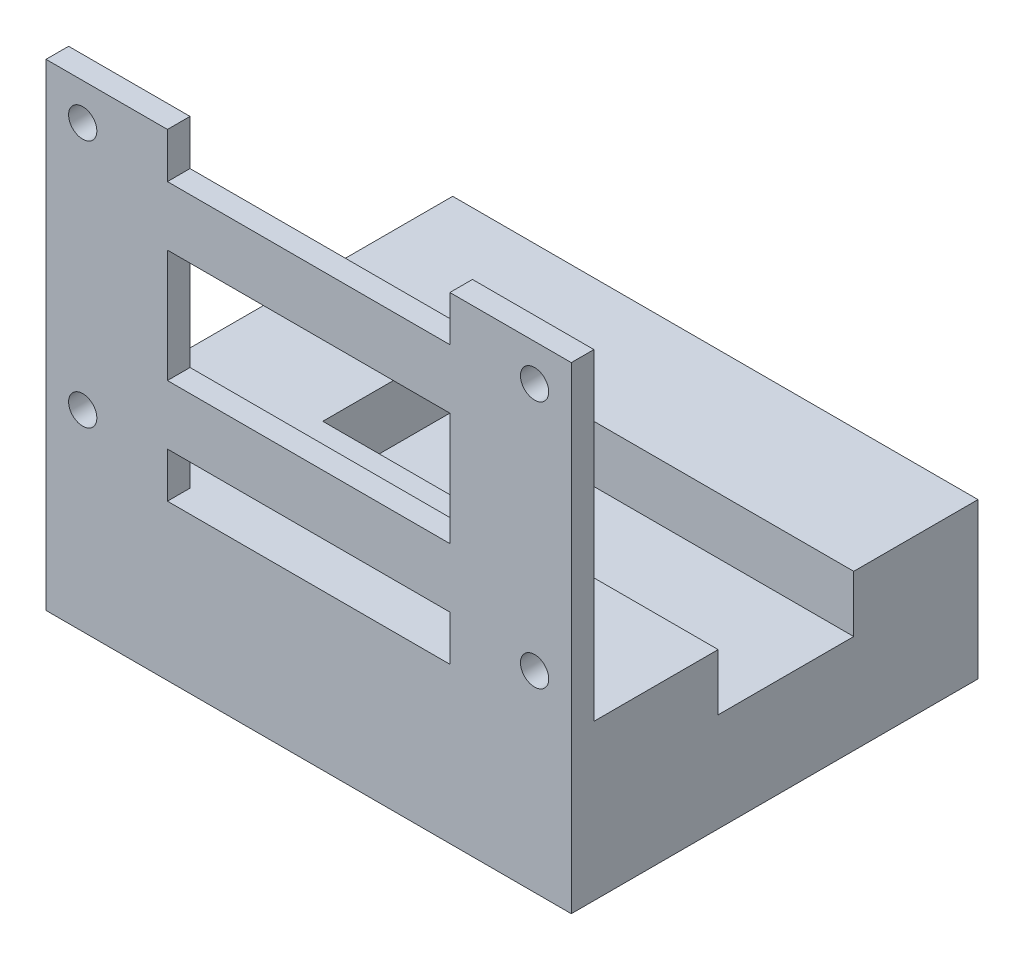
SolidWorks part; units mm, degrees
ref_plane "Front Plane" through (0, 0, 0) normal (0, 0, 1) x (1, 0, 0)
ref_plane "Top Plane" through (0, 0, 0) normal (0, 1, 0) x (1, 0, 0)
ref_plane "Right Plane" through (0, 0, 0) normal (1, 0, 0) x (0, 0, -1)
sketch "Sketch1" plane through (0, 0, 0) normal (0, 1, 0) x (1, 0, 0)
  line L1 (-23.25, -17) -> (23.25, -17)
  line L2 (-23.25, -17) -> (-23.25, 17)
  line L3 (-23.25, 17) -> (23.25, 17)
  line L4 (23.25, -17) -> (23.25, 17)
  line L5 (-23.25, -17) -> (23.25, 17) construction
  line L6 (-23.25, 17) -> (23.25, -17) construction
  point P0 (0, 0)
  dimension "D1" = 46.5
  dimension "D2" = 34
extrude "Boss-Extrude1" add sketch "Sketch1" along normal blind 13.75
sketch "Sketch2" plane through (0, 0, 17) normal (0, 0, 1) x (1, 0, 0)
  line L1 (-23.25, 0) -> (23.25, 0)
  line L2 (-23.25, 0) -> (-23.25, 42.25)
  line L3 (-23.25, 42.25) -> (23.25, 42.25)
  line L4 (23.25, 0) -> (23.25, 42.25)
  dimension "D1" = 46.5
  dimension "D2" = 42.25
extrude "Boss-Extrude2" add sketch "Sketch2" along normal blind 2
sketch "Sketch3" plane through (0, 0, 19) normal (0, 0, 1) x (1, 0, 0)
  line L0 (-23.25, 28) -> (23.25, 28) construction
  line L1 (-12.5, 33) -> (12.5, 33)
  line L2 (-12.5, 33) -> (-12.5, 23)
  line L3 (-12.5, 23) -> (12.5, 23)
  line L4 (12.5, 33) -> (12.5, 23)
  line L5 (23.25, 0) -> (23.25, 42.25) construction
  line L6 (23.25, 42.25) -> (-23.25, 42.25) construction
  line L7 (-23.25, 42.25) -> (-23.25, 0) construction
  circle A0 centre (-20, 39) radius 1.25
  circle A2 centre (20, 39) radius 1.25
  circle A4 centre (20, 17) radius 1.25
  circle A5 centre (-20, 17) radius 1.25
  dimension "D1" = 2.5
  dimension "D11" = 2.5
  dimension "D2" = 10
  dimension "D3" = 25
  dimension "D4" = 5
  dimension "D5" = 10.75
  dimension "D6" = 14.25
  dimension "D7" = 3.25
  dimension "D8" = 3.25
  dimension "D9" = 3.25
  dimension "D10" = 3.25
extrude "Cut-Extrude1" cut sketch "Sketch3" against normal up to next
sketch "Sketch4" plane through (0, 13.75, 0) normal (0, 1, 0) x (1, 0, 0)
  line L0 (23.25, -17) -> (23.25, 17) construction
  line L1 (23.25, 6) -> (-11.75, 6)
  line L2 (23.25, 6) -> (23.25, -6)
  line L3 (23.25, -6) -> (-11.75, -6)
  line L4 (-11.75, 6) -> (-11.75, -6)
  line L5 (23.25, 17) -> (-23.25, 17) construction
  dimension "D1" = 35
  dimension "D2" = 12
  dimension "D3" = 11
extrude "Cut-Extrude2" cut sketch "Sketch4" against normal blind 5
sketch "Sketch6" plane through (0, 0, 0) normal (0, -1, 0) x (1, 0, 0)
  line L0 (16.25, -10) -> (16.25, 12)
  line L1 (23.25, -17) -> (-23.25, -17)
  line L2 (23.25, -17) -> (23.25, 19)
  line L3 (23.25, 19) -> (-23.25, 19)
  line L4 (-23.25, -17) -> (-23.25, 19)
  line L5 (16.25, 12) -> (-16.25, 12)
  line L6 (-16.25, -10) -> (-16.25, 12)
  line L7 (16.25, -10) -> (-16.25, -10)
  circle A0 centre (16.25, -10) radius 2
  circle A1 centre (16.25, 12) radius 2
  circle A2 centre (-16.25, -10) radius 2
  circle A3 centre (-16.25, 12) radius 2
  dimension "D2" = 4
  dimension "D3" = 4
  dimension "D4" = 4
  dimension "D5" = 4
  dimension "D1" = 7
extrude "Cut-Extrude3" cut sketch "Sketch6" against normal blind 10 contours A0 | A1 | A2 | A3
sketch "Sketch7" plane through (0, 0, 17) normal (0, 0, -1) x (-1, 0, 0)
  line L0 (-23.25, 13.75) -> (23.25, 13.75) construction
  line L1 (-12.5, 13.75) -> (12.5, 13.75)
  line L2 (-12.5, 13.75) -> (-12.5, 17.75)
  line L3 (-12.5, 17.75) -> (12.5, 17.75)
  line L4 (12.5, 13.75) -> (12.5, 17.75)
  line L5 (-23.25, 42.25) -> (23.25, 42.25) construction
  line L6 (-12.5, 42.25) -> (12.5, 42.25)
  line L7 (-12.5, 42.25) -> (-12.5, 38.25)
  line L8 (-12.5, 38.25) -> (12.5, 38.25)
  line L9 (12.5, 42.25) -> (12.5, 38.25)
  dimension "D1" = 4
  dimension "D2" = 4
extrude "Cut-Extrude4" cut sketch "Sketch7" against normal blind 10
